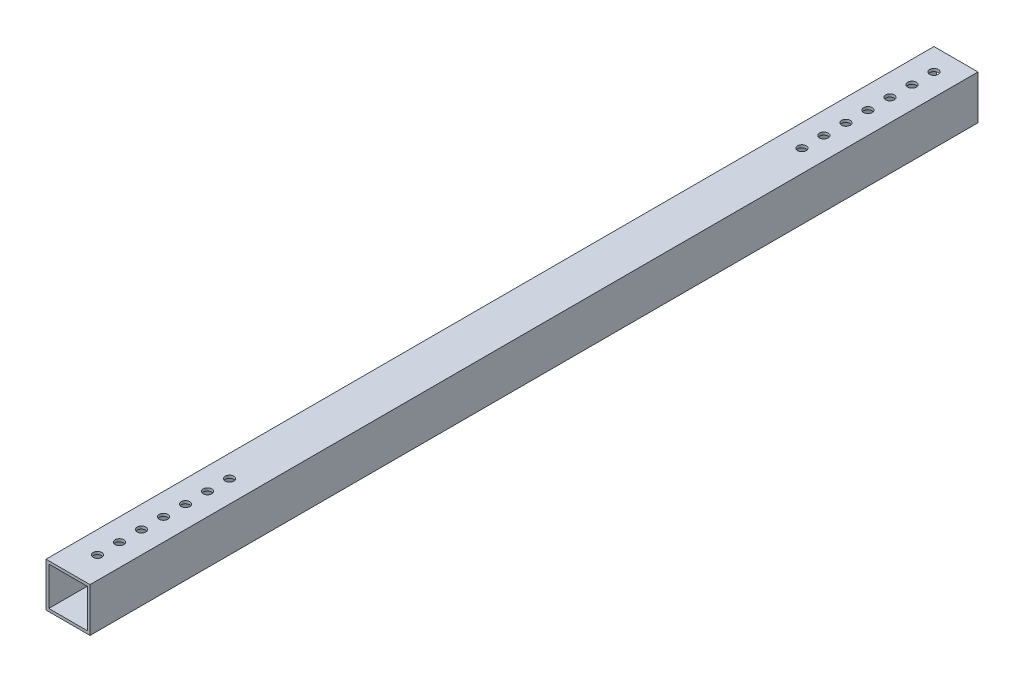
SolidWorks part; units mm, degrees
material "6061-T6 (SS)"
ref_plane "Front Plane" through (0, 0, 0) normal (0, 0, 1) x (1, 0, 0)
ref_plane "Top Plane" through (0, 0, 0) normal (0, 1, 0) x (1, 0, 0)
ref_plane "Right Plane" through (0, 0, 0) normal (1, 0, 0) x (0, 0, -1)
sketch "Sketch1" plane through (0, 0, 0) normal (0, 0, 1) x (1, 0, 0)
  line L1 (-12.7, -12.7) -> (12.7, -12.7)
  line L2 (-12.7, -12.7) -> (-12.7, 12.7)
  line L3 (-12.7, 12.7) -> (12.7, 12.7)
  line L4 (12.7, -12.7) -> (12.7, 12.7)
  line L5 (-12.7, -12.7) -> (12.7, 12.7) construction
  line L6 (-12.7, 12.7) -> (12.7, -12.7) construction
  point P0 (0, 0)
  dimension "D1" = 25.4
  dimension "D2" = 25.4
extrude "Boss-Extrude1" add sketch "Sketch1" along normal mid plane 512.2914
shell "Shell1" thickness 1.5875
sketch "Sketch3" plane through (0, 0, 0) normal (0, 1, 0) x (1, 0, 0)
  line L0 (12.7, 256.1457) -> (-12.7, 256.1457) construction
  circle A0 centre (0, 243.4457) radius 2.4892
  circle A1 centre (0, 230.7457) radius 2.4892
  circle A2 centre (0, 218.0457) radius 2.4892
  circle A3 centre (0, 205.3457) radius 2.4892
  circle A4 centre (0, 192.6457) radius 2.4892
  circle A5 centre (0, 179.9457) radius 2.4892
  circle A6 centre (0, 167.2457) radius 2.4892
  circle A7 centre (0, 154.5457) radius 2.4892 construction
  circle A8 centre (0, 141.8457) radius 2.4892 construction
  circle A9 centre (0, 129.1457) radius 2.4892 construction
  circle A10 centre (0, 116.4457) radius 2.4892 construction
  circle A11 centre (0, 103.7457) radius 2.4892 construction
  circle A12 centre (0, 91.0457) radius 2.4892 construction
  circle A13 centre (0, 78.3457) radius 2.4892 construction
  circle A14 centre (0, 65.6457) radius 2.4892 construction
  circle A15 centre (0, 52.9457) radius 2.4892 construction
  circle A16 centre (0, 40.2457) radius 2.4892 construction
  circle A17 centre (0, 27.5457) radius 2.4892 construction
  circle A18 centre (0, 14.8457) radius 2.4892 construction
  circle A19 centre (0, 2.1457) radius 2.4892 construction
  circle A20 centre (0, -10.5543) radius 2.4892 construction
  circle A21 centre (0, -23.2543) radius 2.4892 construction
  circle A22 centre (0, -35.9543) radius 2.4892 construction
  circle A23 centre (0, -48.6543) radius 2.4892 construction
  circle A24 centre (0, -61.3543) radius 2.4892 construction
  circle A25 centre (0, -74.0543) radius 2.4892 construction
  circle A26 centre (0, -86.7543) radius 2.4892 construction
  circle A27 centre (0, -99.4543) radius 2.4892 construction
  circle A28 centre (0, -112.1543) radius 2.4892 construction
  circle A29 centre (0, -124.8543) radius 2.4892 construction
  circle A30 centre (0, -137.5543) radius 2.4892 construction
  circle A31 centre (0, -150.2543) radius 2.4892 construction
  circle A32 centre (0, -162.9543) radius 2.4892
  circle A33 centre (0, -175.6543) radius 2.4892
  circle A34 centre (0, -188.3543) radius 2.4892
  circle A35 centre (0, -201.0543) radius 2.4892
  circle A36 centre (0, -213.7543) radius 2.4892
  circle A37 centre (0, -226.4543) radius 2.4892
  circle A38 centre (0, -239.1543) radius 2.4892
  point P4 (0, 256.1457)
  dimension "D1" = 4.9784
  dimension "D2" = 12.7
  dimension "D4" = 12.7
  dimension "D3" = 39
extrude "Cut-Extrude1" cut sketch "Sketch3" against normal through all both and the other way through all
